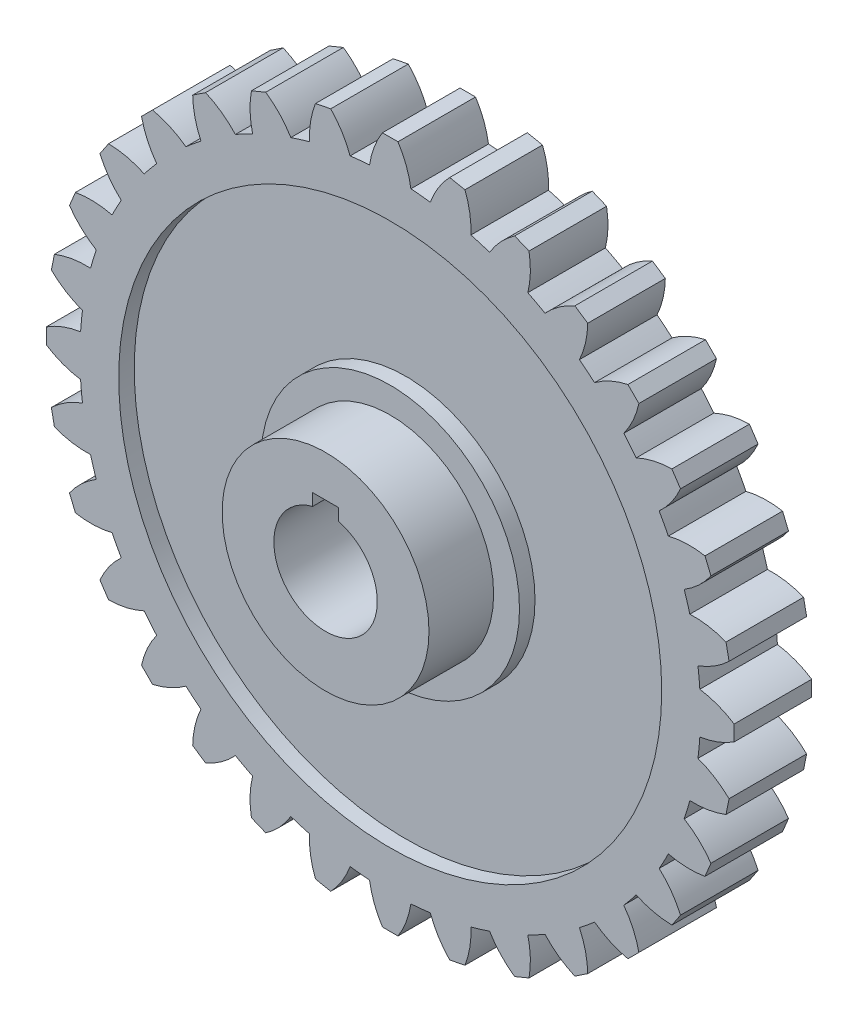
SolidWorks part; units mm, degrees
material "Cast Carbon Steel"
ref_plane "Front Plane" through (0, 0, 0) normal (0, 0, 1) x (1, 0, 0)
ref_plane "Top Plane" through (0, 0, 0) normal (0, 1, 0) x (1, 0, 0)
ref_plane "Right Plane" through (0, 0, 0) normal (1, 0, 0) x (0, 0, -1)
sketch "Sketch1" plane through (0, 0, 0) normal (0, 0, 1) x (1, 0, 0)
  circle A0 centre (0, 0) radius 60
  dimension "D1" = 120
extrude "Boss-Extrude1" add sketch "Sketch1" along normal mid plane 15
sketch "Sketch2" plane through (0, 0, 7.5) normal (0, 0, 1) x (1, 0, 0)
  line L0 (0, 60) -> (0, 66.5) construction
  line L1 (-1.5, 66.5) -> (1.5, 66.5)
  circle A0 centre (0, 0) radius 60 construction
  arc A1 (4, 59.8665) -> (-4, 59.8665) centre (0, 0) ccw
  arc A2 (-1.5, 66.5) -> (-4, 59.8665) centre (12.8082, 57.3198) ccw
  arc A3 (1.5, 66.5) -> (4, 59.8665) centre (-12.8082, 57.3198) cw
  point P7 (0, 66.5)
  dimension "D3" = 17
  dimension "D1" = 6.5
  dimension "D2" = 3
  dimension "D4" = 8
extrude "Boss-Extrude2" add sketch "Sketch2" against normal up to surface (15 mm away) up to face at (60, 0, -7.5)
pattern_circular "CirPattern1" count 32 over 360 about axis through (0, 0, 0) along (0, 0, 1) of "Boss-Extrude2"
sketch "Sketch3" plane through (0, 0, 0) normal (0, 0, 1) x (1, 0, 0)
  circle A0 centre (0, 0) radius 20
  dimension "D1" = 40
extrude "Boss-Extrude3" add sketch "Sketch3" along normal mid plane 40
sketch "Sketch4" plane through (0, 0, 20) normal (0, 0, 1) x (1, 0, 0)
  line L0 (0, 0) -> (0, 12) construction
  line L1 (-2.5, 12) -> (2.5, 12)
  line L2 (2.5, 12) -> (2.5, 9.6825)
  line L3 (-2.5, 12) -> (-2.5, 9.6825)
  arc A0 (-2.5, 9.6825) -> (2.5, 9.6825) centre (0, 0) ccw
  point P7 (0, 12)
  dimension "D2" = 20
  dimension "D1" = 5
  dimension "D3" = 12
extrude "Cut-Extrude1" cut sketch "Sketch4" against normal through all both and the other way through all
sketch "Sketch5" plane through (0, 0, 0) normal (0, 0, 1) x (1, 0, 0)
  circle A1 centre (0, 0) radius 52.5
  circle A2 centre (0, 0) radius 25
  circle A3 centre (0, 0) radius 25
  dimension "D2" = 105
  dimension "D1" = 5
extrude "Cut-Extrude2" cut sketch "Sketch5" against normal blind 3 and the other way through all from surface at 7.5 starting at face at (20, 0, 7.5)
mirror "Mirror1" about plane through (0, 0, 0) normal (0, 0, 1) of "Cut-Extrude2"
